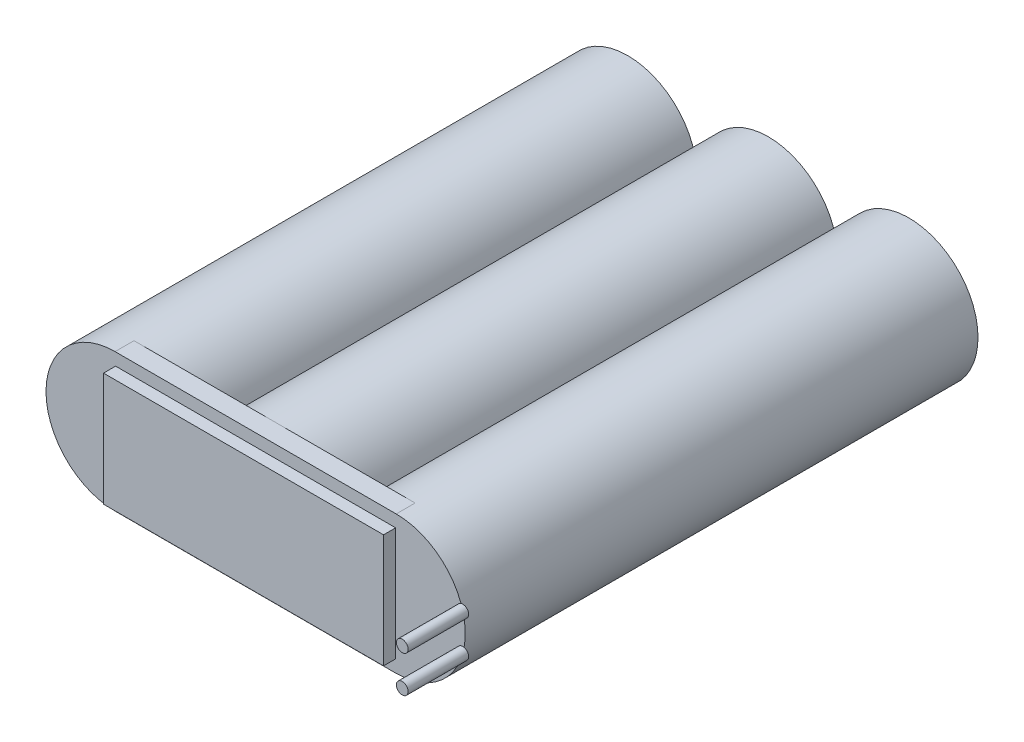
SolidWorks part; units mm, degrees
ref_plane "Front Plane" through (0, 0, 0) normal (0, 0, 1) x (1, 0, 0)
ref_plane "Top Plane" through (0, 0, 0) normal (0, 1, 0) x (1, 0, 0)
ref_plane "Right Plane" through (0, 0, 0) normal (1, 0, 0) x (0, 0, -1)
sketch "Sketch1" plane through (0, 0, 0) normal (0, 0, 1) x (1, 0, 0)
  line L0 (-18.575, 0) -> (18.575, 0) construction
  circle A0 centre (0, 0) radius 9.125
  circle A1 centre (18.575, 0) radius 9.125
  circle A2 centre (-18.575, 0) radius 9.125
  point P7 (27.7, 0)
  point P8 (-27.7, 0)
  dimension "D1" = 18.25
  dimension "D2" = 55.4
extrude "Boss-Extrude1" add sketch "Sketch1" along normal mid plane 65.25
sketch "Sketch2" plane through (0, 0, 32.625) normal (0, 0, 1) x (1, 0, 0)
  line L0 (-18.575, 0) -> (18.575, 0) construction
  line L1 (-18.575, 9.125) -> (18.575, 9.125)
  line L2 (-18.575, -9.125) -> (18.575, -9.125)
  arc A0 (-18.575, 9.125) -> (-18.575, -9.125) centre (-18.575, 0) ccw
  arc A1 (18.575, -9.125) -> (18.575, 9.125) centre (18.575, 0) ccw
  circle A2 centre (18.575, 0) radius 9.125 construction
  point P4 (0, 0)
  point P9 (18.575, 9.125)
extrude "Boss-Extrude2" add sketch "Sketch2" along normal blind 2.5
sketch "Sketch3" plane through (0, 0, 35.125) normal (0, 0, 1) x (1, 0, 0)
  line L1 (-18.5, -7.5) -> (18.5, -7.5)
  line L2 (-18.5, -7.5) -> (-18.5, 7.5)
  line L3 (-18.5, 7.5) -> (18.5, 7.5)
  line L4 (18.5, -7.5) -> (18.5, 7.5)
  line L5 (-18.5, -7.5) -> (18.5, 7.5) construction
  line L6 (-18.5, 7.5) -> (18.5, -7.5) construction
  point P0 (0, 0)
  dimension "D1" = 37
  dimension "D2" = 15
extrude "Boss-Extrude3" add sketch "Sketch3" along normal blind 1.6
sketch "Sketch4" plane through (0, 0, 35.125) normal (0, 0, 1) x (1, 0, 0)
  line L0 (27.3733, 2.42) -> (27.3733, -2.42) construction
  line L1 (27.3733, 0) -> (27.7, 0) construction
  circle A0 centre (27.3733, 2.42) radius 0.775
  circle A1 centre (27.3733, -2.42) radius 0.775
  arc A2 (18.575, -9.125) -> (18.575, 9.125) centre (18.575, 0) ccw construction
  dimension "D1" = 1.55
  dimension "D2" = 4.84
extrude "Boss-Extrude4" add sketch "Sketch4" along normal blind 8
